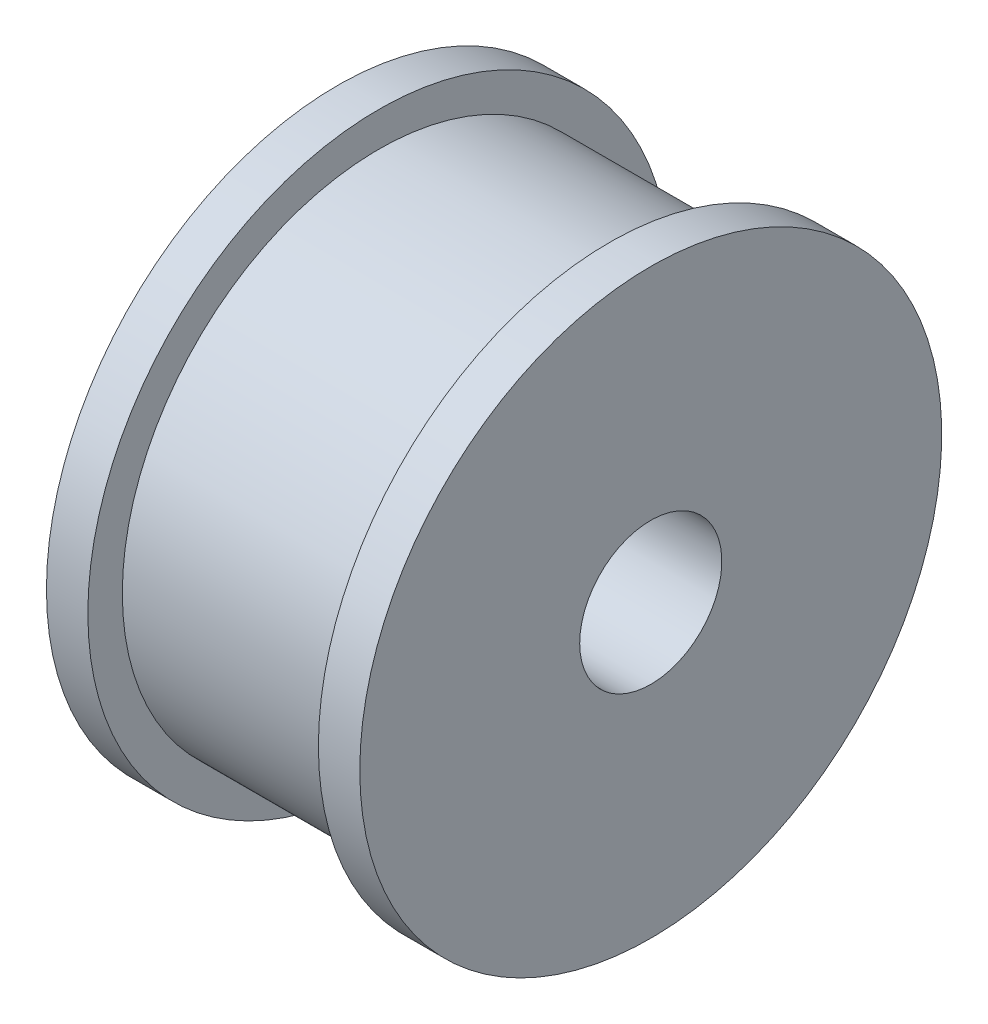
SolidWorks part; units mm, degrees
ref_plane "Front Plane" through (0, 0, 0) normal (0, 0, 1) x (1, 0, 0)
ref_plane "Top Plane" through (0, 0, 0) normal (0, 1, 0) x (1, 0, 0)
ref_plane "Right Plane" through (0, 0, 0) normal (1, 0, 0) x (0, 0, -1)
sketch "Sketch1" plane through (0, 0, 0) normal (0, 1, 0) x (1, 0, 0)
  line L0 (0, -11.46) -> (-5.15, -11.46)
  line L1 (-5.15, -13) -> (-7, -13)
  line L2 (-7, -13) -> (-7, 0)
  line L3 (7, 0) -> (7, -13)
  line L4 (7, -13) -> (5.15, -13)
  line L5 (5.15, -13) -> (5.15, -11.46)
  line L6 (5.15, -11.46) -> (0, -11.46)
  line L7 (-5.15, -11.46) -> (-5.15, -13)
  line L8 (-7, 0) -> (7, 0) construction
  line L9 (7, 0) -> (-7, 0)
  dimension "D1" = 13
  dimension "D2" = 1.85
  dimension "D3" = 7
  dimension "D4" = 11.46
  dimension "D5" = 7
  dimension "D6" = 1.85
revolve "Revolve1" add sketch "Sketch1" angle 360 about L8
hole_wizard "1/4 (0.25) Diameter Hole1" positions "Sketch5" profile "Sketch4" hole size "1/4" standard "ANSI Inch" end condition through all
sketch "Sketch5" plane through (-7, 0, 0) normal (-1, 0, 0) x (0, 0, 1)
  point P0 (0, 0)
sketch "Sketch4" plane through (-7, 0, 0) normal (0, 1, 0) x (0, 0, 1)
  line L0 (0, 0) -> (0, 14)
  line L1 (0, 14) -> (3.175, 14)
  line L2 (3.175, 14) -> (3.175, 0)
  line L5 (3.175, 0) -> (0, 0)
  line L11 (0, -6.35) -> (0, 107.95) construction
  dimension "Thru Hole Dia." = 6.35
  dimension "Thru Hole Depth" = 14
